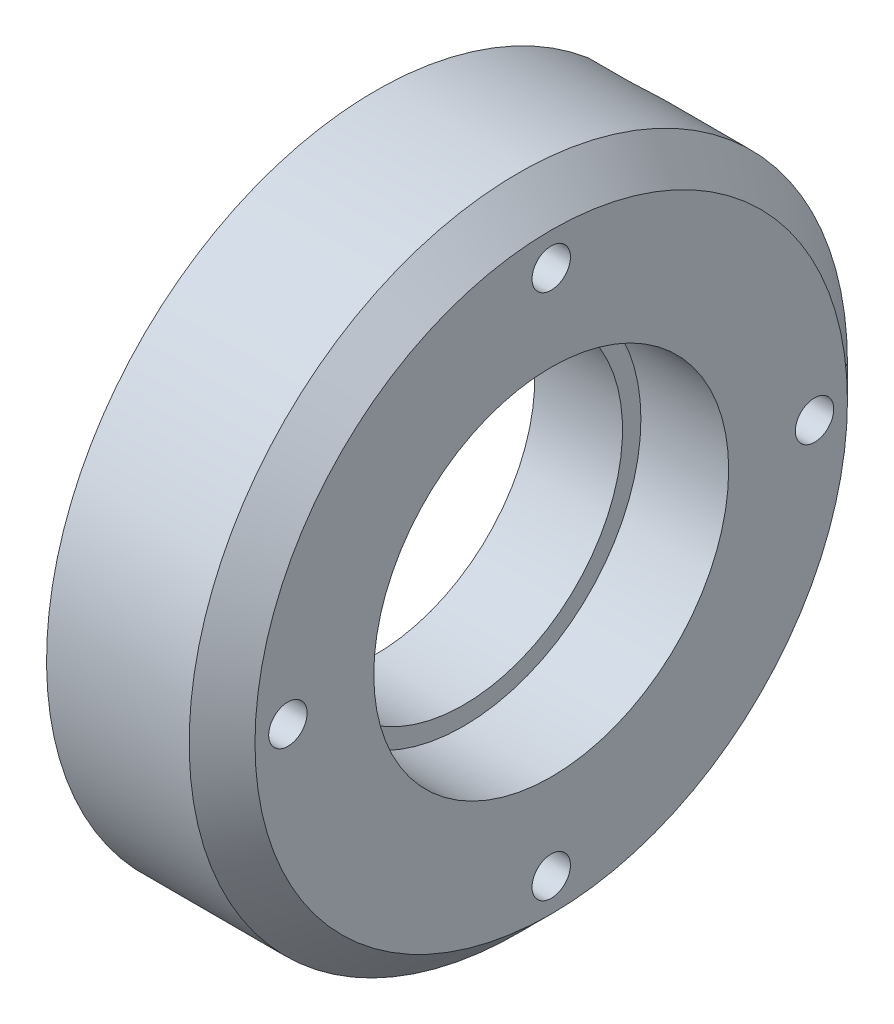
SolidWorks part; units mm, degrees
ref_plane "Спереди" through (0, 0, 0) normal (0, 0, 1) x (1, 0, 0)
ref_plane "Сверху" through (0, 0, 0) normal (0, 1, 0) x (1, 0, 0)
ref_plane "Справа" through (0, 0, 0) normal (1, 0, 0) x (0, 0, -1)
sketch "Эскиз1" plane through (0, 0, 0) normal (1, 0, 0) x (0, 0, -1)
  circle A0 centre (0, 0) radius 32
  arc A1 (6.2657, 10.2343) -> (6.2657, -10.2343) centre (0, 0) ccw
  arc A2 (10.2343, 6.2657) -> (6.2657, 10.2343) centre (9, 9) ccw
  arc A3 (6.2657, -10.2343) -> (10.2343, -6.2657) centre (9, -9) ccw
  circle A4 centre (-24, 9) radius 3
  circle A5 centre (-24, -9) radius 3
  arc A6 (10.2343, -6.2657) -> (10.2343, 6.2657) centre (0, 0) ccw
  dimension "D1" = 64
  dimension "D2" = 24
  dimension "D3" = 18
  dimension "D5" = 6
  dimension "D4" = 33
  dimension "D6" = 9
extrude "Бобышка-Вытянуть1" add sketch "Эскиз1" along normal blind 5
sketch "Эскиз2" plane through (5, 0, 0) normal (1, 0, 0) x (0, 0, -1)
  circle A0 centre (0, 0) radius 30
  circle A1 centre (0, 0) radius 16.175
  dimension "D1" = 32.35
  dimension "D2" = 60
extrude "Бобышка-Вытянуть2" add sketch "Эскиз2" along normal blind 35
sketch "Эскиз4" plane through (5, 0, 0) normal (1, 0, 0) x (0, 0, -1)
  circle A0 centre (0, 0) radius 14
  circle A1 centre (0, 0) radius 17
  dimension "D1" = 34
extrude "Бобышка-Вытянуть4" add sketch "Эскиз4" along normal blind 5
sketch "Эскиз8" plane through (5, 0, 0) normal (1, 0, 0) x (0, 0, -1)
  line L0 (-18, -20) -> (18, -20) construction
  line L1 (0, 0) -> (23.1658, 0) construction
  line L2 (18, 20) -> (0, 0) construction
  line L3 (0, 0) -> (-18, -20) construction
  line L4 (-18, -20) -> (-18, 20) construction
  line L5 (-18, 20) -> (0, 0) construction
  line L6 (0, 0) -> (18, -20) construction
  line L7 (0, 0) -> (0, -20) construction
  circle A0 centre (-18, -20) radius 1.5
  circle A1 centre (18, -20) radius 1.5
  circle A2 centre (18, 20) radius 1.5
  circle A3 centre (-18, 20) radius 1.5
  dimension "D4" = 3
  dimension "D2" = 20
  dimension "D3" = 36
extrude "Вырез-Вытянуть1" cut sketch "Эскиз8" against normal blind 10
sketch "Эскиз13" plane through (5, 0, 0) normal (-1, 0, 0) x (0, 0, 1)
  circle A0 centre (24, 9) radius 3.1675
  circle A1 centre (24, -9) radius 3
  arc A2 (-6.1213, 10.3213) -> (-10.3213, 6.1213) centre (-9, 9) ccw
  arc A3 (-10.3213, -6.1213) -> (-6.1213, -10.3213) centre (-9, -9) ccw
  arc A4 (-6.1213, 10.3213) -> (-10.3213, 6.1213) centre (0, 0) ccw
  arc A5 (-10.3213, -6.1213) -> (-6.1213, -10.3213) centre (0, 0) ccw
extrude "Бобышка-Вытянуть5" add sketch "Эскиз13" along normal blind 2
sketch "Эскиз14" plane through (40, 0, 0) normal (1, 0, 0) x (0, 0, -1)
  circle A0 centre (0, 0) radius 34.6268
extrude "Вырез-Вытянуть5" cut sketch "Эскиз14" against normal blind 10
sketch "Эскиз17" plane through (30, 0, 0) normal (1, 0, 0) x (0, 0, -1)
  line L0 (-24, 0) -> (0, 0) construction
  line L1 (0, 0) -> (24, 0) construction
  circle A0 centre (-24, 0) radius 1.75
  circle A1 centre (24, 0) radius 1.75 construction
  circle A2 centre (0, 24) radius 1.75
  circle A3 centre (24, 0) radius 1.75
  circle A4 centre (0, -24) radius 1.75
  point P15 (0, 0)
  dimension "D1" = 3.5
  dimension "D2" = 24
  dimension "D3" = 4
extrude "Вырез-Вытянуть7" cut sketch "Эскиз17" against normal blind 25
sketch "Эскиз18" plane through (0, 0, 0) normal (-1, 0, 0) x (0, 0, 1)
  circle A0 centre (0, 0) radius 32
extrude "Вырез-Вытянуть8" cut sketch "Эскиз18" against normal blind 17
sketch "Эскиз19" plane through (17, 0, 0) normal (-1, 0, 0) x (0, 0, 1)
  circle A0 centre (0, 0) radius 16.3
  circle A1 centre (0, 0) radius 14.5
  dimension "D1" = 29
  dimension "D2" = 32.6
extrude "Бобышка-Вытянуть6" add sketch "Эскиз19" against normal blind 5
sketch "Эскиз21" plane through (17, 0, 0) normal (-1, 0, 0) x (0, 0, 1)
  circle A0 centre (-24, 0) radius 3
  circle A1 centre (24, 0) radius 3
  dimension "D1" = 6
extrude "Вырез-Вытянуть10" [suppressed] cut sketch "Эскиз21" against normal blind 2
sketch "Эскиз22" plane through (17, 0, 0) normal (-1, 0, 0) x (0, 0, 1)
  circle A0 centre (0, 0) radius 16.5
  circle A1 centre (0, 0) radius 14.5
  dimension "D1" = 33
  dimension "D2" = 29
extrude "Бобышка-Вытянуть7" add sketch "Эскиз22" along normal blind 3
sketch "Эскиз23" plane through (17, 0, 0) normal (-1, 0, 0) x (0, 0, 1)
  circle A0 centre (0, 0) radius 16.5
  circle A1 centre (-24, 0) radius 1.75
  circle A2 centre (0, 24) radius 1.75
  circle A3 centre (24, 0) radius 1.75
  circle A4 centre (0, -24) radius 1.75
  circle A5 centre (0, 0) radius 30
  dimension "D1" = 33
  dimension "D2" = 3.5
extrude "Бобышка-Вытянуть8" add sketch "Эскиз23" along normal blind 3
sketch "Эскиз24" plane through (30, 0, 0) normal (1, 0, 0) x (0, 0, -1)
  line L0 (16.2635, 16.2635) -> (0, 0) construction
  line L1 (0, 0) -> (-16.2635, -16.2635) construction
  line L2 (0, 0) -> (0, -24) construction
  circle A0 centre (16.2635, 16.2635) radius 2
  circle A1 centre (-16.2635, -16.2635) radius 2
  dimension "D1" = 4
  dimension "D2" = 4
  dimension "D3" = 23
  dimension "D4" = 45
extrude "Вырез-Вытянуть11" [suppressed] cut sketch "Эскиз24" against normal blind 3
chamfer "Фаска1" [suppressed] distance 3 angle 5
sketch "Эскиз25" plane through (14, 0, 0) normal (-1, 0, 0) x (0, 0, 1)
  line L1 (0, 0) -> (-21.2132, -21.2132) construction
  line L2 (-21.2132, -21.2132) -> (0, -30) construction
  line L3 (0, -30) -> (0, 0) construction
  circle A1 centre (0, 0) radius 30 construction
  dimension "D1" = 45
chamfer "Фаска2" distance 3 angle 45 1 edges at (30, 0, -30)
sketch3d "Трехмерный эскиз1"
  line L0 (14, 0, 0) -> (14, -21.2132, -21.2132) construction
sketch "Эскиз26" plane through (0, 0, 0) normal (0, -0.7071, 0.7071) x (1, 0, 0)
  line L0 (14, 0) -> (30, 0) construction
  line L1 (12, 2.5) -> (17, 2.5)
  line L2 (12, 2.5) -> (12, -2.5)
  line L3 (12, -2.5) -> (17, -2.5)
  line L4 (14, -21.2132) -> (14, 0) construction
  line L5 (14, 0) -> (14, -30) construction
  line L6 (30, -27) -> (30, 27) construction
  line L7 (14, 30) -> (14, -30) construction
  arc A0 (17, -2.5) -> (17, 2.5) centre (17, 0) ccw
  dimension "D1" = 2.5
  dimension "D2" = 3
  dimension "D3" = 5
extrude "Вырез-Вытянуть12" cut sketch "Эскиз26" against normal through all
